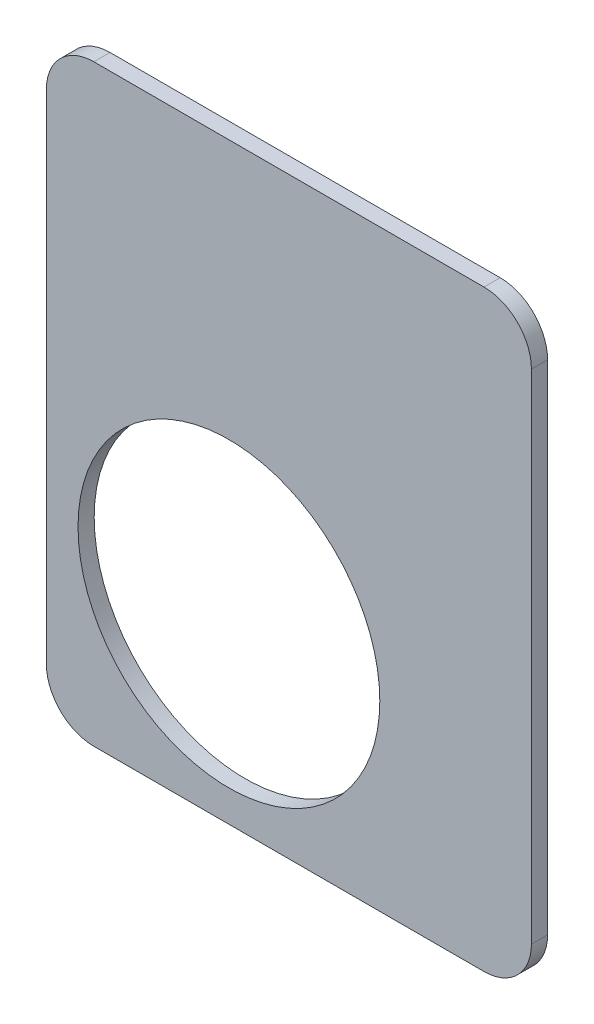
SolidWorks part; units mm, degrees
ref_plane "Front Plane" through (0, 0, 0) normal (0, 0, 1) x (1, 0, 0)
ref_plane "Top Plane" through (0, 0, 0) normal (0, 1, 0) x (1, 0, 0)
ref_plane "Right Plane" through (0, 0, 0) normal (1, 0, 0) x (0, 0, -1)
sketch "Sketch1" plane through (0, 0, 0) normal (0, 0, 1) x (1, 0, 0)
  line L1 (-112.4167, 111.8218) -> (249.5833, 111.8218)
  line L2 (-156.4167, 67.8218) -> (-156.4167, -394.1782)
  line L3 (-112.4167, -438.1782) -> (249.5833, -438.1782)
  line L4 (293.5833, 67.8218) -> (293.5833, -394.1782)
  line L5 (-156.4167, 111.8218) -> (293.5833, -438.1782) construction
  line L6 (-156.4167, -438.1782) -> (293.5833, 111.8218) construction
  arc A0 (-112.4167, 111.8218) -> (-156.4167, 67.8218) centre (-112.4167, 67.8218) ccw
  arc A1 (-112.4167, -438.1782) -> (-156.4167, -394.1782) centre (-112.4167, -394.1782) cw
  arc A2 (293.5833, 67.8218) -> (249.5833, 111.8218) centre (249.5833, 67.8218) ccw
  arc A3 (293.5833, -394.1782) -> (249.5833, -438.1782) centre (249.5833, -394.1782) cw
  point P0 (68.5833, -163.1782)
  point P8 (-621.3013, 16.3919)
  dimension "D5" = 44
  dimension "D6" = 44
  dimension "D7" = 44
  dimension "D8" = 44
  dimension "D1" = 68.5833
  dimension "D2" = 293.5833
  dimension "D3" = 111.8218
  dimension "D4" = 163.1782
extrude "Boss-Extrude1" add sketch "Sketch1" along normal blind 15 contours A3 L3 A1 L2 A0 L1 A2 L4
sketch "Sketch2" plane through (0, 0, 15) normal (0, 0, 1) x (1, 0, 0)
sketch "Sketch7" plane through (0, 0, 15) normal (0, 0, 1) x (1, 0, 0)
  circle A0 centre (12.913, -269.0215) radius 156
  circle A1 centre (12.913, -269.0215) radius 140
extrude "Cut-Extrude3" cut sketch "Sketch7" against normal blind 15 contours A1
